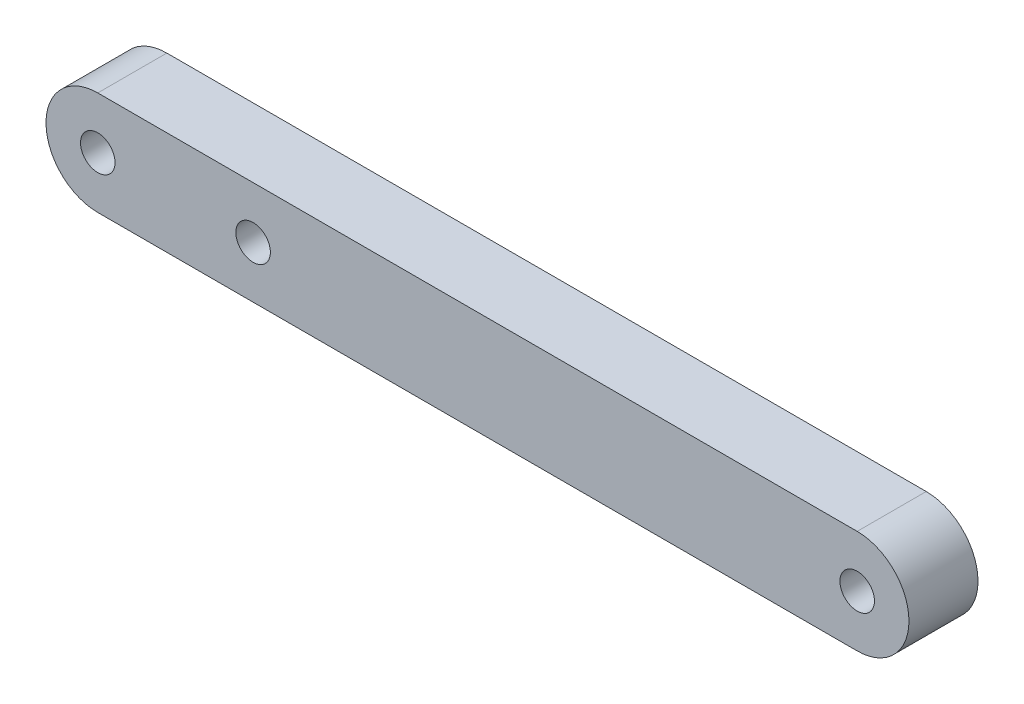
SolidWorks part; units mm, degrees
ref_plane "Front Plane" through (0, 0, 0) normal (0, 0, 1) x (1, 0, 0)
ref_plane "Top Plane" through (0, 0, 0) normal (0, 1, 0) x (1, 0, 0)
ref_plane "Right Plane" through (0, 0, 0) normal (1, 0, 0) x (0, 0, -1)
sketch "Sketch1" plane through (0, 0, 0) normal (0, 0, 1) x (1, 0, 0)
  line L0 (0, -7.5) -> (110, -7.5)
  line L1 (0, 7.5) -> (110, 7.5)
  circle A0 centre (0, 0) radius 2.5
  circle A1 centre (22.5, 0) radius 2.5
  circle A2 centre (110, 0) radius 2.5
  arc A3 (0, 7.5) -> (0, -7.5) centre (0, 0) ccw
  arc A4 (110, -7.5) -> (110, 7.5) centre (110, 0) ccw
  dimension "D2" = 5
  dimension "D3" = 5
  dimension "D4" = 5
  dimension "D6" = 7.5
  dimension "D1" = 22.5
  dimension "D5" = 110
extrude "Boss-Extrude1" add sketch "Sketch1" along normal blind 10
